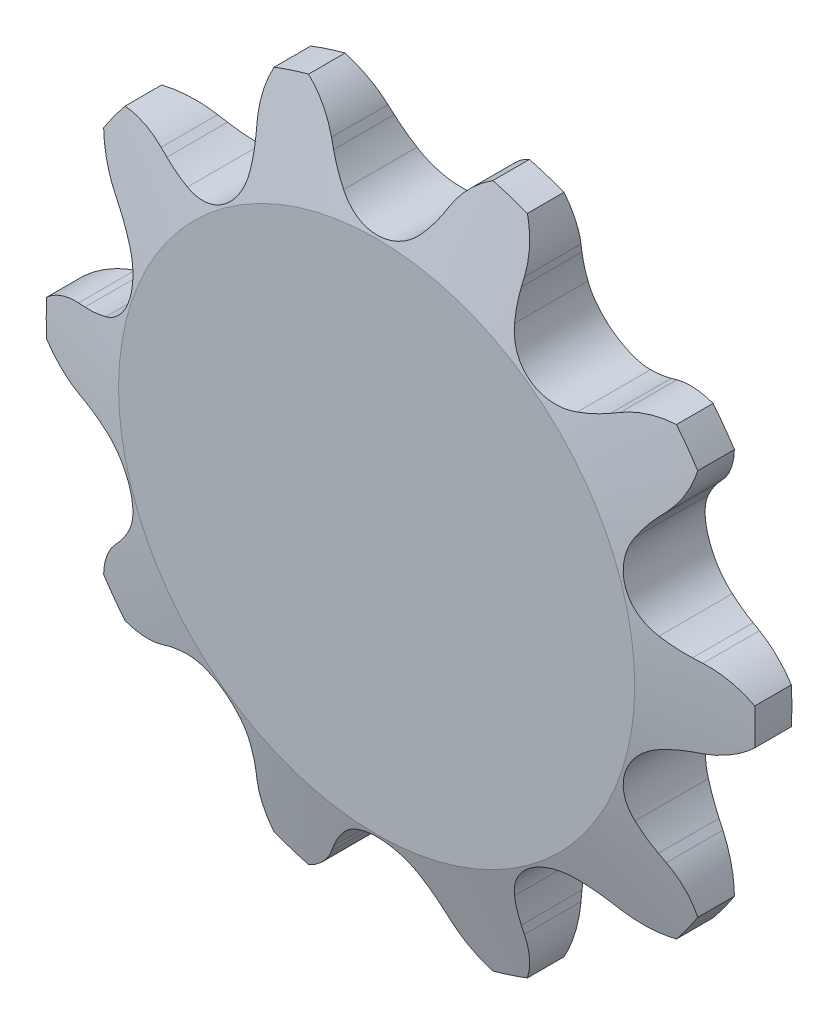
SolidWorks part; units mm, degrees
ref_plane "Front Plane" through (0, 0, 0) normal (0, 0, 1) x (1, 0, 0)
ref_plane "Top Plane" through (0, 0, 0) normal (0, 1, 0) x (1, 0, 0)
ref_plane "Right Plane" through (0, 0, 0) normal (1, 0, 0) x (0, 0, -1)
sketch "Chain Data" plane through (0, 0, 0) normal (0, 0, 1) x (1, 0, 0)
  line L0 (-518.2469, 244.3179) -> (-28.9136, 244.3179) construction
  line L1 (-162.9516, 66.321) -> (221.7151, 66.321) construction
  text T0 "Source: https://evmc2.files.wordpress.com/2012/03/picture-1.png"
ref_axis "Centaur" through (0, 0, -87.4025) along (0, 0, 1)
sketch "Profile Master" plane through (0, 0, 0) normal (0, 0, 1) x (1, 0, 0)
  line L0 (0, 0) -> (0, 39.9687) construction
  line L1 (24.02, 10.2745) -> (-24.02, 10.2745) construction
  line L2 (-24.02, 12.0076) -> (24.02, 12.0076) construction
  line L3 (1.9936, 0) -> (1.9936, 39.9687) construction
  line L4 (1.9936, 12.0076) -> (-1.6608, 8.8308) construction
  line L5 (1.9936, 12.0076) -> (-1.8159, 9.9305) construction
  line L6 (-1.8159, 9.9305) -> (-2.8589, 11.8435) construction
  line L7 (-4.3965, 0) -> (-4.3965, 39.9687) construction
  line L8 (-24.02, 8.846) -> (24.02, 8.846) construction
  line L9 (0, 0) -> (-12.459, 38.3449) construction
  circle A0 centre (0, 0) radius 10.2745
  circle A1 centre (0, 10.2745) radius 1.6899
  arc A2 (-1.2754, 9.1658) -> (-1.8159, 9.9305) centre (1.977, 12.0379) cw
  circle A3 centre (-4.3965, 8.846) radius 2.7849
  point P7 (0, 10.2745)
  point P13 (-1.2754, 9.1658)
  point P17 (1.9936, 12.0076)
  point P22 (-3.7548, 11.556)
  point P27 (-4.3965, 8.846)
  dimension "D8" = 4.339
  dimension "D4" = 1.9936
  dimension "D10" = 1.4285
  dimension "D12" = 18
sketch "Tooth Profile" plane through (0, 0, 0) normal (0, 0, 1) x (1, 0, 0)
  line L0 (-1.8159, 9.9305) -> (-2.8589, 11.8435) construction
  line L1 (-1.8159, 9.9305) -> (-1.9514, 10.1791)
  line L2 (0, 0) -> (0, 39.9687) construction
  line L3 (0, 0) -> (0, 39.9687) construction
  line L4 (1.8159, 9.9305) -> (1.9514, 10.1791)
  circle A0 centre (0, 10.2745) radius 1.6899 construction
  arc A1 (-1.8159, 9.9305) -> (-1.2754, 9.1658) centre (1.977, 12.0379) ccw construction
  circle A2 centre (-4.3965, 8.846) radius 2.7849 construction
  arc A3 (-1.2754, 9.1658) -> (1.2754, 9.1658) centre (0, 10.2745) ccw
  arc A4 (-1.8159, 9.9305) -> (-1.2754, 9.1658) centre (1.977, 12.0379) ccw
  arc A5 (-1.9514, 10.1791) -> (-3.7548, 11.556) centre (-4.3965, 8.846) ccw
  arc A6 (1.9514, 10.1791) -> (3.7548, 11.556) centre (4.3965, 8.846) cw
  arc A7 (1.8159, 9.9305) -> (1.2754, 9.1658) centre (-1.977, 12.0379) cw
  arc A8 (3.7548, 11.556) -> (-3.7548, 11.556) centre (0, 0) ccw
  point P19 (-3.7548, 11.556)
sketch "OD Sketch" plane through (0, 0, 0) normal (0, 0, 1) x (1, 0, 0)
  line L0 (0, 10.2745) -> (-6.0392, 8.3123) construction
  line L1 (-3.0196, 9.2934) -> (-3.6083, 11.1051) construction
  arc A0 (-1.2754, 9.1658) -> (1.2754, 9.1658) centre (0, 10.2745) ccw construction
  circle A1 centre (0, 0) radius 10.2745 construction
  circle A2 centre (0, 0) radius 11.6766
  point P0 (0, 10.2745)
  dimension "D1" = 6.35
  dimension "D2" = 1.905
sketch "Sketch7" plane through (0, 0, 0) normal (1, 0, 0) x (0, 0, -1)
  line L0 (0, 11.6766) -> (0, -11.6766) construction
  line L1 (-1.397, 0) -> (1.397, 0)
  line L2 (-1.397, 0) -> (-1.397, 8.5016)
  line L3 (-1.397, 8.5016) -> (1.397, 8.5016) construction
  line L4 (1.397, 0) -> (1.397, 8.5016)
  line L5 (-1.397, 8.5016) -> (1.397, 8.5016) construction
  line L6 (-1.397, 8.5016) -> (-1.397, 11.6766) construction
  line L7 (-1.397, 11.6766) -> (1.397, 11.6766) construction
  line L8 (1.397, 8.5016) -> (1.397, 11.6766) construction
  line L9 (0, 11.6766) -> (0, -11.6766) construction
  line L10 (0.6033, 11.6766) -> (-0.6033, 11.6766)
  line L11 (-0.6033, 11.6766) -> (-1.397, 8.5016)
  line L12 (0.6033, 11.6766) -> (1.397, 8.5016)
  point P1 (0, 11.6766)
  point P4 (0, 0)
  point P16 (0, 11.6766)
  dimension "D1" = 2.794
  dimension "D2" = 3.175
  dimension "D3" = 0.7937
revolve "Revolve1" add sketch "Sketch7" angle 360 about axis through (0, 0, -87.4025) along (0, 0, 1)
extrude "Cut-Extrude1" cut sketch "Tooth Profile" along normal through all both and the other way through all
pattern_circular "CirPattern3" count 10 over 360 about axis through (0, 0, 0) along (0, 0, 1) of "Cut-Extrude1"
sketch "Pitch Diamiter" plane through (0, 0, 0) normal (0, 0, 1) x (1, 0, 0)
  circle A0 centre (0, 0) radius 10.2745
  dimension "D1" = 20.549
equation "\"D1@Profile Master\" = \"PD\""
equation "\"ChainNo\"= 25'Can only be 25 or 35"
equation "\"N\"= 10'# Of teeth"
equation "\"P\"= IIF ( \"ChainNo\" = 25 , 0.25 , IIF ( \"ChainNo\" = 35 , 0.375 , 0.25 ) )'Pitch"
equation "\"PD\"= ( \"P\" ) / sin ( 180 / \"N\" )'Sprocket Pitch Diamiter"
equation "\"Dr\"= IIF ( \"ChainNo\" = 25 , 0.13 , IIF ( \"ChainNo\" = 35 , 0.2 , 0.13 ) )'Roller Diamiter"
equation "\"Ds\"= ( 1.0005 * \"Dr\" ) + .003"
equation "\"R\"= \"Ds\" / 2"
equation "\"D2@Profile Master\" = \"Ds\""
equation "\"M\"= ( .8 * \"Dr\" ) * ( cos ( 35 + ( 60 / \"N\" ) ) )"
equation "\"T\"= ( .8 * \"Dr\" ) * ( sin ( 35 + ( 60 / \"N\" ) ) )"
equation "\"D3@Profile Master\" = \"T\""
equation "\"D4@Profile Master\" = \"M\""
equation "\"A\"= 35 + ( 60 / \"N\" )"
equation "\"B\"= 18 - ( 56 / \"N\" )"
equation "\"E\"= ( 1.3025 * \"Dr\" ) + 0.0015"
equation "\"D5@Profile Master\" = \"A\""
equation "\"D6@Profile Master\" = \"E\""
equation "\"D7@Profile Master\" = \"B\""
equation "\"D8@Profile Master\" = \"E\""
equation "\"W\"= ( 1.4 * \"Dr\" ) * cos ( 180 / \"N\" )"
equation "\"V\"= ( 1.4 * \"Dr\" ) * sin ( 180 / \"N\" )"
equation "\"D9@Profile Master\" = \"W\""
equation "\"D10@Profile Master\" = \"V\""
equation "\"F\"= \"Dr\" * ( .8 * cos ( 18 - ( 56 / \"N\" ) ) + 1.4 * cos ( 17 - ( 64 / \"N\" ) ) - 1.3025 ) - .0015"
equation "\"D11@Profile Master\" = \"F\""
equation "\"D12@Profile Master\" = 180 / \"N\""
equation "\"D1@CirPattern3\"=\"N\""
equation "\"Thick\"= IIF ( \"ChainNo\" = 25 , 0.11 , IIF ( \"ChainNo\" = 35 , 0.168 , 0.11 ) )'Sprocket Thickness"
equation "\"D1@OD Sketch\" = \"P\""
equation "\"D2@OD Sketch\" = \"P\" * .3"
equation "\"D1@Sketch7\"=\"Thick\""
equation "\"D2@Sketch7\"=\"P\"/2"
equation "\"D3@Sketch7\"=\"P\"/8"
equation "\"D1@Pitch Diamiter\" = \"PD\""
